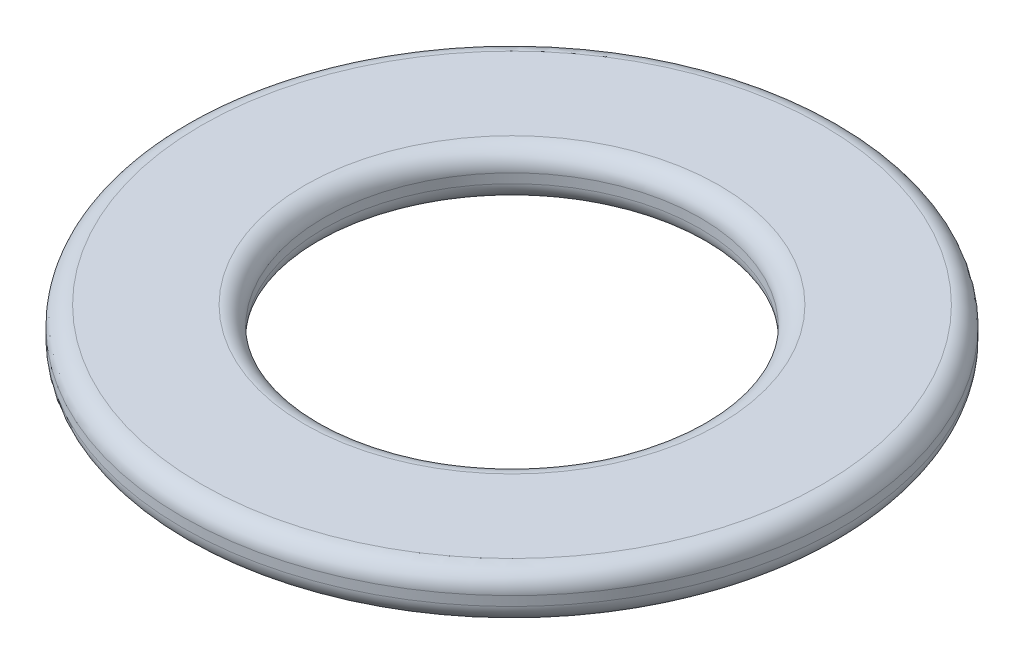
SolidWorks part; units mm, degrees
ref_plane "Front Plane" through (0, 0, 0) normal (0, 0, 1) x (1, 0, 0)
ref_plane "Top Plane" through (0, 0, 0) normal (0, 1, 0) x (1, 0, 0)
ref_plane "Right Plane" through (0, 0, 0) normal (1, 0, 0) x (0, 0, -1)
sketch "Sketch1" plane through (0, 0, 0) normal (0, 1, 0) x (1, 0, 0)
  circle A0 centre (0, 0) radius 5.08
  circle A1 centre (0, 0) radius 8.89
  dimension "D1" = 10.16
  dimension "D2" = 17.78
extrude "Boss-Extrude1" add sketch "Sketch1" along normal blind 1.27
fillet "Fillet1" radius 0.508 4 edges at (0, 0, 5.08) (0, 0, 8.89) (0, 1.27, 5.08) (0, 1.27, 8.89)
